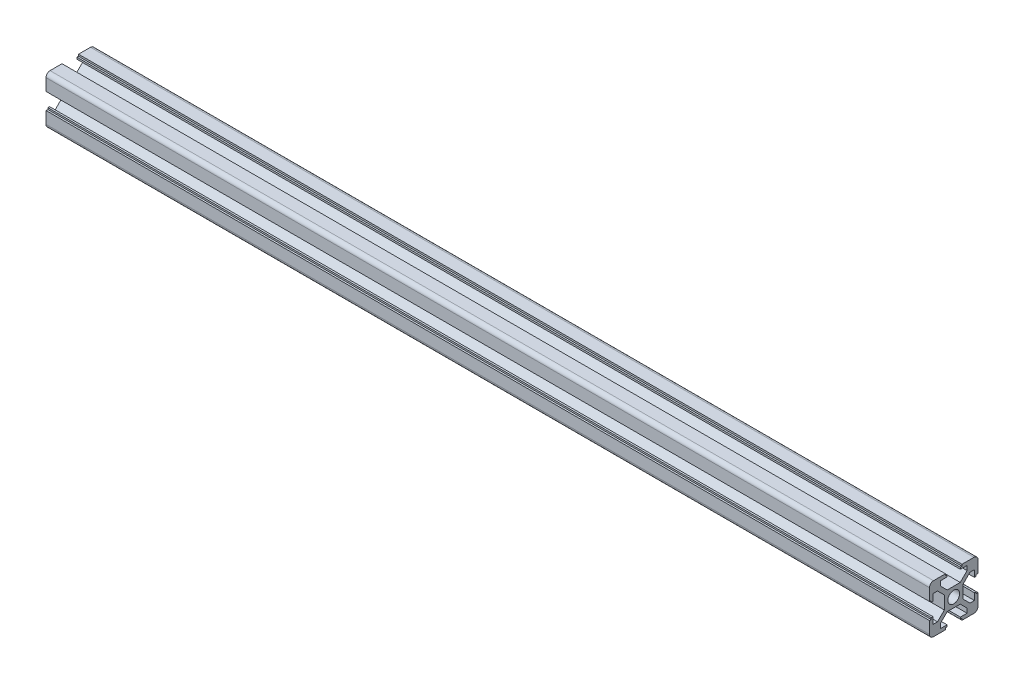
SolidWorks part; units mm, degrees
material "6061-T6 (SS)"
ref_plane "Front Plane" through (0, 0, 0) normal (0, 0, 1) x (1, 0, 0)
ref_plane "Top Plane" through (0, 0, 0) normal (0, 1, 0) x (1, 0, 0)
ref_plane "Right Plane" through (0, 0, 0) normal (1, 0, 0) x (0, 0, -1)
sketch "Sketch1" plane through (0, 0, 0) normal (0, 0, 1) x (1, 0, 0)
  line L0 (-273.05, 0) -> (273.05, 0)
  point P4 (0, 0)
  dimension "D1" = 546.1
other "Boschrexroth BOSCH_30X30_V2(1)"
ref_plane "Plane1" through (-273.05, 0, 0) normal (1, 0, 0) x (0, 1, 0)
sketch "Sketch11" plane through (-273.05, 0, 0) normal (1, 0, 0) x (0, 1, 0)
  line L0 (0, 0) -> (0, 15) construction
  line L1 (0, 5.8) -> (-4.03, 5.8)
  line L2 (-15, 0) -> (0, 0) construction
  line L3 (-4.03, 5.8) -> (-8.25, 10.02)
  line L4 (-8.25, 10.02) -> (-8.25, 12.8)
  line L5 (-8.25, 12.8) -> (-4.1, 12.8)
  line L6 (-4.1, 12.8) -> (-4.1, 13.9)
  line L7 (-4.1, 13.9) -> (-5.1, 13.9)
  line L8 (-5.1, 13.9) -> (-5.1, 15)
  line L9 (-5.1, 15) -> (-12.5, 15)
  line L10 (-15, 12.5) -> (-15, 5.1)
  line L11 (-15, 5.1) -> (-13.9, 5.1)
  line L12 (-13.9, 5.1) -> (-13.9, 4.1)
  line L13 (-13.9, 4.1) -> (-12.8, 4.1)
  line L14 (-12.8, 4.1) -> (-12.8, 8.25)
  line L15 (-12.8, 8.25) -> (-10.02, 8.25)
  line L16 (-10.02, 8.25) -> (-5.8, 4.03)
  line L17 (-5.8, 4.03) -> (-5.8, 0)
  line L18 (4.1, 13.9) -> (5.1, 13.9)
  line L19 (5.1, 13.9) -> (5.1, 15)
  line L20 (10.02, 8.25) -> (5.8, 4.03)
  line L21 (12.8, 8.25) -> (10.02, 8.25)
  line L22 (12.8, 4.1) -> (12.8, 8.25)
  line L23 (13.9, 4.1) -> (12.8, 4.1)
  line L24 (13.9, 5.1) -> (13.9, 4.1)
  line L25 (15, 5.1) -> (13.9, 5.1)
  line L26 (15, 12.5) -> (15, 5.1)
  line L27 (5.1, 15) -> (12.5, 15)
  line L28 (8.25, 12.8) -> (4.1, 12.8)
  line L29 (8.25, 10.02) -> (8.25, 12.8)
  line L30 (4.03, 5.8) -> (8.25, 10.02)
  line L31 (4.1, 13.9) -> (4.1, 12.8)
  line L32 (4.03, 5.8) -> (0, 5.8)
  line L33 (5.8, 4.03) -> (5.8, 0)
  line L34 (4.1, -13.9) -> (4.1, -12.8)
  line L35 (4.1, -13.9) -> (5.1, -13.9)
  line L36 (5.1, -13.9) -> (5.1, -15)
  line L37 (4.03, -5.8) -> (8.25, -10.02)
  line L38 (8.25, -10.02) -> (8.25, -12.8)
  line L39 (8.25, -12.8) -> (4.1, -12.8)
  line L40 (5.1, -15) -> (12.5, -15)
  line L41 (15, -12.5) -> (15, -5.1)
  line L42 (15, -5.1) -> (13.9, -5.1)
  line L43 (13.9, -5.1) -> (13.9, -4.1)
  line L44 (13.9, -4.1) -> (12.8, -4.1)
  line L45 (12.8, -4.1) -> (12.8, -8.25)
  line L46 (12.8, -8.25) -> (10.02, -8.25)
  line L47 (10.02, -8.25) -> (5.8, -4.03)
  line L48 (5.8, 0) -> (5.8, -4.03)
  line L49 (-13.9, -4.1) -> (-12.8, -4.1)
  line L50 (-13.9, -5.1) -> (-13.9, -4.1)
  line L51 (-15, -5.1) -> (-13.9, -5.1)
  line L52 (-10.02, -8.25) -> (-5.8, -4.03)
  line L53 (-12.8, -8.25) -> (-10.02, -8.25)
  line L54 (-12.8, -4.1) -> (-12.8, -8.25)
  line L55 (-15, -12.5) -> (-15, -5.1)
  line L56 (-5.1, -15) -> (-12.5, -15)
  line L57 (-5.1, -13.9) -> (-5.1, -15)
  line L58 (-4.1, -13.9) -> (-5.1, -13.9)
  line L59 (-4.1, -12.8) -> (-4.1, -13.9)
  line L60 (-8.25, -12.8) -> (-4.1, -12.8)
  line L61 (-8.25, -10.02) -> (-8.25, -12.8)
  line L62 (-4.03, -5.8) -> (-8.25, -10.02)
  line L63 (-5.8, 0) -> (-5.8, -4.03)
  line L64 (-4.03, -5.8) -> (4.03, -5.8)
  line L65 (0, 0) -> (15, 0) construction
  line L66 (0, 0) -> (0, -15) construction
  arc A0 (-12.5, 15) -> (-15, 12.5) centre (-12.5, 12.5) ccw
  arc A1 (-15, -12.5) -> (-12.5, -15) centre (-12.5, -12.5) ccw
  arc A2 (12.5, -15) -> (15, -12.5) centre (12.5, -12.5) ccw
  arc A3 (15, 12.5) -> (12.5, 15) centre (12.5, 12.5) ccw
  circle A4 centre (0, 0) radius 3.65
  point P69 (-15, 15)
  point P72 (-15, -15)
  point P75 (15, -15)
  point P78 (15, 15)
  point P79 (-15, 15)
  point P81 (15, 15)
  point P83 (15, -15)
  point P84 (-15, -15)
  point P86 (0, 0)
  dimension "D15" = 2.5
  dimension "D16" = 7.3
  dimension "D1" = 15
  dimension "D2" = 2.2
  dimension "D3" = 1.1
  dimension "D4" = 1
  dimension "D5" = 8.25
  dimension "D6" = 5.1
  dimension "D7" = 7
  dimension "D8" = 2.78
  dimension "D9" = 15
  dimension "D10" = 15
  dimension "D11" = 4.03
  dimension "D12" = 4.03
  dimension "D13" = 2.5032
  dimension "D14" = 9.2
